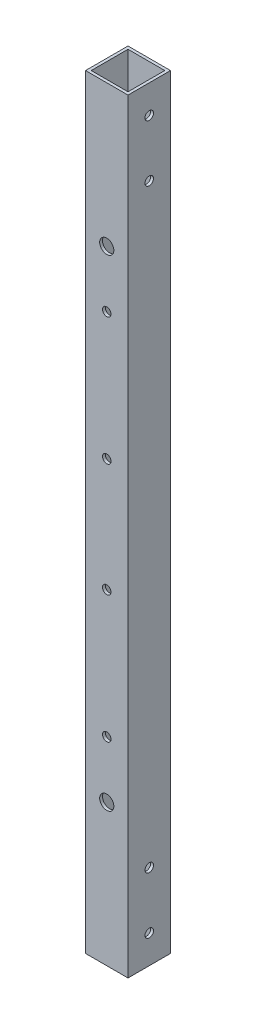
SolidWorks part; units mm, degrees
material "6061-O (SS)"
ref_plane "前视基准面" through (0, 0, 0) normal (0, 0, 1) x (1, 0, 0)
ref_plane "上视基准面" through (0, 0, 0) normal (0, 1, 0) x (1, 0, 0)
ref_plane "右视基准面" through (0, 0, 0) normal (1, 0, 0) x (0, 0, -1)
sketch "草图1" plane through (0, 0, 0) normal (0, 1, 0) x (1, 0, 0)
  line L0 (-6.5, 6.5) -> (6.5, 6.5)
  line L1 (-7.5, -7.5) -> (7.5, -7.5)
  line L2 (-7.5, -7.5) -> (-7.5, 7.5)
  line L3 (-7.5, 7.5) -> (7.5, 7.5)
  line L4 (7.5, -7.5) -> (7.5, 7.5)
  line L5 (-7.5, -7.5) -> (7.5, 7.5) construction
  line L6 (-7.5, 7.5) -> (7.5, -7.5) construction
  line L7 (6.5, -6.5) -> (6.5, 6.5)
  line L8 (-6.5, -6.5) -> (6.5, -6.5)
  line L9 (-6.5, -6.5) -> (-6.5, 6.5)
  point P0 (0, 0)
  dimension "D1" = 15
  dimension "D2" = 1
extrude "凸台-拉伸1" add sketch "草图1" along normal blind 270
sketch "草图2" plane through (0, 0, 7.5) normal (0, 0, 1) x (1, 0, 0)
  line L0 (0, 270) -> (0, 0) construction
  line L1 (-7.5, 270) -> (7.5, 270) construction
  line L2 (-7.5, 135) -> (7.5, 135) construction
  line L3 (-7.5, 270) -> (-7.5, 0) construction
  line L4 (7.5, 270) -> (7.5, 0) construction
  circle A0 centre (0, 155) radius 1.5
  circle A1 centre (0, 115) radius 1.5
  circle A2 centre (0, 200) radius 1.5
  circle A3 centre (0, 70) radius 1.5
  circle A4 centre (0, 220) radius 2.5
  circle A5 centre (0, 50) radius 2.5
  dimension "D1" = 40
  dimension "D2" = 45
  dimension "D3" = 3
  dimension "D4" = 170
  dimension "D5" = 5
extrude "切除-拉伸1" cut sketch "草图2" against normal through all
sketch "草图3" plane through (7.5, 0, 0) normal (1, 0, 0) x (0, 0, -1)
  line L0 (0, 270) -> (0, 0) construction
  line L1 (-7.5, 270) -> (7.5, 270) construction
  line L2 (-7.5, 135) -> (7.5, 135) construction
  line L3 (-7.5, 270) -> (-7.5, 0) construction
  line L4 (7.5, 270) -> (7.5, 0) construction
  circle A0 centre (0, 240) radius 1.5
  circle A1 centre (0, 30) radius 1.5
  circle A2 centre (0, 10) radius 1.5
  circle A3 centre (0, 260) radius 1.5
  dimension "D1" = 210
  dimension "D2" = 20
  dimension "D3" = 3
extrude "切除-拉伸2" cut sketch "草图3" against normal through all
